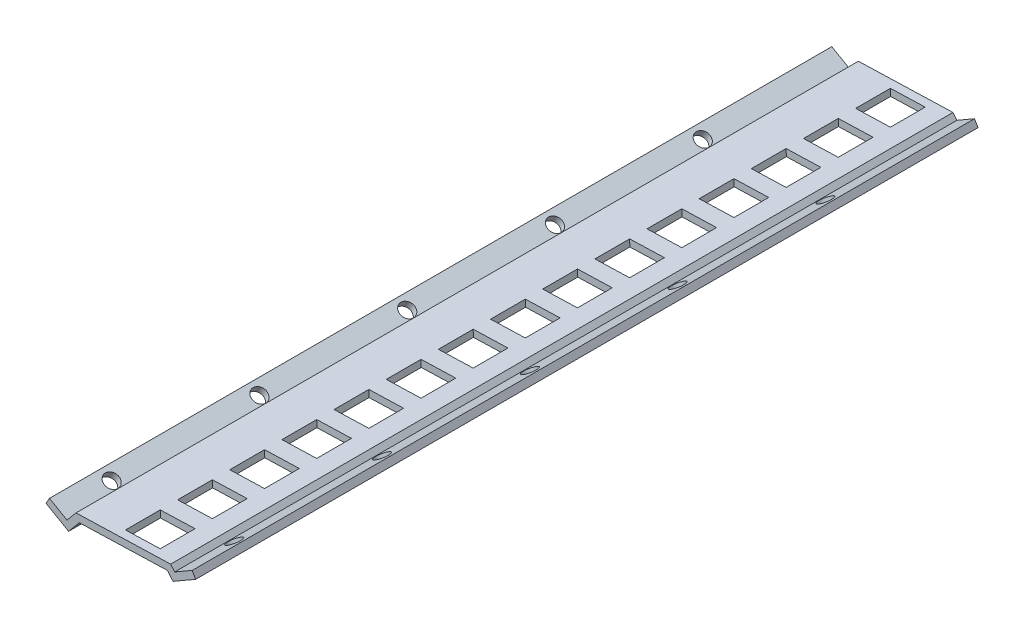
SolidWorks part; units mm, degrees
ref_plane "Front Plane" through (0, 0, 0) normal (0, 0, 1) x (1, 0, 0)
ref_plane "Top Plane" through (0, 0, 0) normal (0, 1, 0) x (1, 0, 0)
ref_plane "Right Plane" through (0, 0, 0) normal (1, 0, 0) x (0, 0, -1)
sketch "Sketch1" plane through (0, 0, 0) normal (0, 0, 1) x (1, 0, 0)
  line L0 (-7.5607, -2.2972) -> (8.7664, -1.7887)
  line L1 (8.7664, -1.7887) -> (9.4578, -2.6126)
  line L2 (9.4578, -2.6126) -> (12.4829, -0.866)
  line L3 (-7.5607, -2.2972) -> (-9.1175, -4.1524)
  line L4 (-9.1175, -4.1524) -> (-12.1426, -2.4059)
  line L5 (9.1858, -4.1553) -> (13.0829, -1.9053)
  line L6 (8.2216, -3.0062) -> (9.1858, -4.1553)
  line L7 (-6.9867, -3.4799) -> (8.2216, -3.0062)
  line L8 (-6.9867, -3.4799) -> (-8.8455, -5.6951)
  line L9 (-8.8455, -5.6951) -> (-12.7426, -3.4451)
  line L10 (13.0829, -1.9053) -> (12.4829, -0.866)
  line L11 (-12.1426, -2.4059) -> (-12.7426, -3.4451)
  line L12 (6.7957, -5.5352) -> (13.0829, -1.9053) construction
  line L13 (-15.4113, -1.9043) -> (-9.1242, -5.5342) construction
  line L15 (-7.1326, -17.6898) -> (6.8606, -17.2539) construction
  line L16 (-12.2753, -6.8158) -> (-8.0994, 0.4171) construction
  line L17 (12.6236, -5.286) -> (9.169, 0.6976) construction
  dimension "D1" = 4.5
  dimension "D2" = 4.5
  dimension "D3" = 100
  dimension "D4" = 120
  dimension "D5" = 100
  dimension "D6" = 2.0881
  dimension "D8" = 1.5
  dimension "D9" = 2.09
  dimension "D7" = 1.2
extrude "Boss-Extrude1" add sketch "Sketch1" along normal blind 171
sketch "Sketch2" plane through (3.4957, -6.0548, 0) normal (-0.5, 0.866, 0) x (0.866, 0.5, 0)
  line L0 (10.3775, -171) -> (6.8844, -171) construction
  line L1 (10.3775, -171) -> (10.3775, 0) construction
  circle A0 centre (8.3775, -162) radius 1.25
  dimension "D1" = 2.5
  dimension "D3" = 2
  dimension "D2" = 9
extrude "Cut-Extrude1" cut sketch "Sketch2" against normal blind 10 contours A0
sketch "Sketch4" plane through (-4.0774, -7.0623, 0) normal (0.5, 0.866, 0) x (0.866, -0.5, 0)
  line L0 (-9.3128, -171) -> (-9.3128, 0) construction
  line L1 (-5.8197, -171) -> (-9.3128, -171) construction
  circle A0 centre (-7.3128, -162) radius 1.25
  dimension "D1" = 2
  dimension "D2" = 2.5
  dimension "D3" = 9
extrude "Cut-Extrude2" cut sketch "Sketch4" against normal blind 10
pattern_linear "LPattern1" count 7 spacing 25.5 along (0, 0, -1) of "Cut-Extrude2", "Cut-Extrude1"
sketch "Sketch5" plane through (0.0642, -2.0597, 0) normal (-0.0311, 0.9995, 0) x (0.9995, 0.0311, 0)
  line L0 (8.7065, -171) -> (-7.6286, -171) construction
  line L1 (-0.5935, -163.5) -> (5.4065, -163.5)
  line L2 (-0.5935, -163.5) -> (-0.5935, -169.5)
  line L3 (-0.5935, -169.5) -> (5.4065, -169.5)
  line L4 (5.4065, -163.5) -> (5.4065, -169.5)
  line L5 (8.7065, -171) -> (8.7065, 0) construction
  point P4 (5.4065, -166.5)
  dimension "D1" = 4.5
  dimension "D2" = 6
  dimension "D3" = 6
  dimension "D4" = 3.3
extrude "Cut-Extrude3" cut sketch "Sketch5" against normal blind 10
pattern_linear "LPattern2" count 19 spacing 9 along (0, 0, -1) of "Cut-Extrude3"
sketch "Sketch6" plane through (0, 0, 0) normal (0, 0, -1) x (-1, 0, 0)
  line L1 (19.3008, 2.0536) -> (-20.106, 2.0536)
  line L2 (19.3008, 2.0536) -> (19.3008, -8.0576)
  line L3 (19.3008, -8.0576) -> (-20.106, -8.0576)
  line L4 (-20.106, 2.0536) -> (-20.106, -8.0576)
extrude "Cut-Extrude4" cut sketch "Sketch6" against normal blind 36
